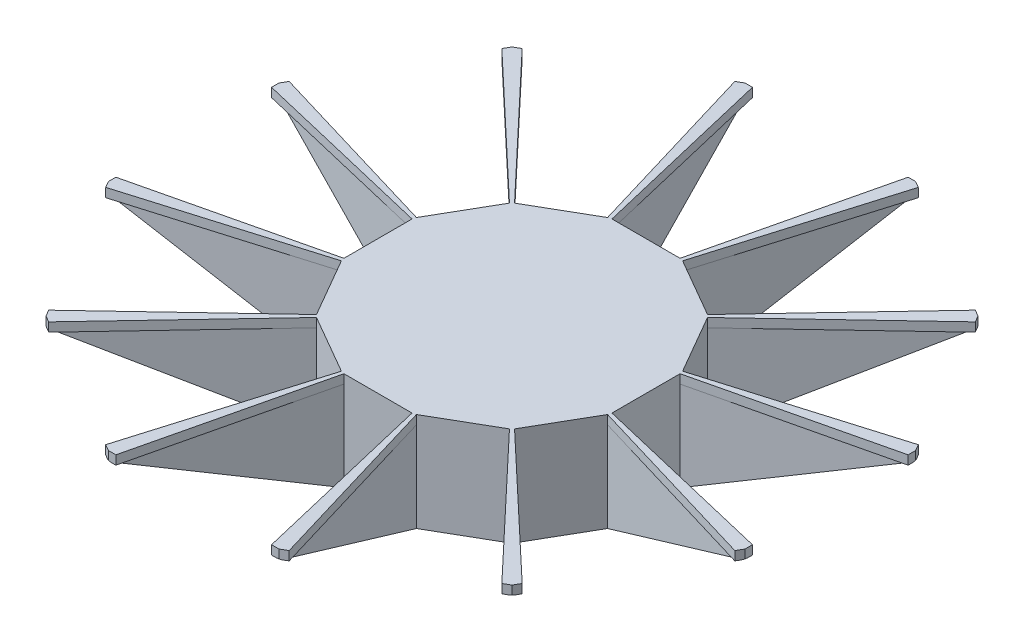
SolidWorks part; units mm, degrees
material "6061 Alloy"
ref_plane "Front Plane" through (0, 0, 0) normal (0, 0, 1) x (1, 0, 0)
ref_plane "Top Plane" through (0, 0, 0) normal (0, 1, 0) x (1, 0, 0)
ref_plane "Right Plane" through (0, 0, 0) normal (1, 0, 0) x (0, 0, -1)
sketch "Sketch1" plane through (0, 0, 0) normal (0, 1, 0) x (1, 0, 0)
  line L0 (-54.641, -54.641) -> (-20, -74.641) construction
  line L1 (54.641, 54.641) -> (20, 74.641) construction
  line L2 (20, 74.641) -> (-20, 74.641) construction
  line L3 (-20, 74.641) -> (-54.641, 54.641) construction
  line L4 (-54.641, 54.641) -> (-74.641, 20) construction
  line L5 (-74.641, 20) -> (-74.641, -20) construction
  line L6 (-74.641, -20) -> (-54.641, -54.641) construction
  line L7 (-20, -74.641) -> (20, -74.641) construction
  line L8 (20, -74.641) -> (54.641, -54.641) construction
  line L9 (54.641, -54.641) -> (74.641, -20) construction
  line L10 (74.641, -20) -> (74.641, 20) construction
  line L11 (74.641, 20) -> (54.641, 54.641) construction
  line L12 (-51.0863, 175.2019) -> (-20.8966, 74.1234)
  line L25 (47.5, 177.2724) -> (-47.5, 177.2724) construction
  line L26 (-47.5, 177.2724) -> (-129.7724, 129.7724) construction
  line L27 (-129.7724, 129.7724) -> (-177.2724, 47.5) construction
  line L28 (-177.2724, 47.5) -> (-177.2724, -47.5) construction
  line L29 (-177.2724, -47.5) -> (-129.7724, -129.7724) construction
  line L30 (-129.7724, -129.7724) -> (-47.5, -177.2724) construction
  line L31 (-47.5, -177.2724) -> (47.5, -177.2724) construction
  line L32 (47.5, -177.2724) -> (129.7724, -129.7724) construction
  line L33 (129.7724, -129.7724) -> (177.2724, -47.5) construction
  line L34 (177.2724, -47.5) -> (177.2724, 47.5) construction
  line L35 (177.2724, 47.5) -> (129.7724, 129.7724) construction
  line L36 (129.7724, 129.7724) -> (47.5, 177.2724) construction
  line L37 (-43.3589, 177.2724) -> (-18.9647, 74.641)
  line L38 (0, 0) -> (-47.5, 177.2724) construction
  line L39 (51.0863, 175.2019) -> (20.8966, 74.1234)
  line L40 (43.3589, 177.2724) -> (18.9647, 74.641)
  line L41 (131.843, 126.1861) -> (55.1587, 53.7444)
  line L42 (126.1861, 131.843) -> (53.7444, 55.1587)
  line L43 (177.2724, 43.3589) -> (74.641, 18.9647)
  line L44 (175.2019, 51.0863) -> (74.1234, 20.8966)
  line L45 (175.2019, -51.0863) -> (74.1234, -20.8966)
  line L46 (177.2724, -43.3589) -> (74.641, -18.9647)
  line L47 (126.1861, -131.843) -> (53.7444, -55.1587)
  line L48 (131.843, -126.1861) -> (55.1587, -53.7444)
  line L49 (43.3589, -177.2724) -> (18.9647, -74.641)
  line L50 (51.0863, -175.2019) -> (20.8966, -74.1234)
  line L51 (-51.0863, -175.2019) -> (-20.8966, -74.1234)
  line L52 (-43.3589, -177.2724) -> (-18.9647, -74.641)
  line L53 (-131.843, -126.1861) -> (-55.1587, -53.7444)
  line L54 (-126.1861, -131.843) -> (-53.7444, -55.1587)
  line L55 (-177.2724, -43.3589) -> (-74.641, -18.9647)
  line L56 (-175.2019, -51.0863) -> (-74.1234, -20.8966)
  line L57 (-175.2019, 51.0863) -> (-74.1234, 20.8966)
  line L58 (-177.2724, 43.3589) -> (-74.641, 18.9647)
  line L59 (-126.1861, 131.843) -> (-53.7444, 55.1587)
  line L60 (-131.843, 126.1861) -> (-55.1587, 53.7444)
  line L61 (-51.0863, 175.2019) -> (-47.5, 177.2724)
  line L62 (-47.5, 177.2724) -> (-43.3589, 177.2724)
  line L63 (43.3589, 177.2724) -> (47.5, 177.2724)
  line L64 (47.5, 177.2724) -> (51.0863, 175.2019)
  line L65 (126.1861, 131.843) -> (129.7724, 129.7724)
  line L66 (129.7724, 129.7724) -> (131.843, 126.1861)
  line L67 (175.2019, 51.0863) -> (177.2724, 47.5)
  line L68 (177.2724, 47.5) -> (177.2724, 43.3589)
  line L69 (177.2724, -43.3589) -> (177.2724, -47.5)
  line L70 (177.2724, -47.5) -> (175.2019, -51.0863)
  line L71 (131.843, -126.1861) -> (129.7724, -129.7724)
  line L72 (129.7724, -129.7724) -> (126.1861, -131.843)
  line L73 (51.0863, -175.2019) -> (47.5, -177.2724)
  line L74 (47.5, -177.2724) -> (43.3589, -177.2724)
  line L75 (-43.3589, -177.2724) -> (-47.5, -177.2724)
  line L76 (-47.5, -177.2724) -> (-51.0863, -175.2019)
  line L77 (-126.1861, -131.843) -> (-129.7724, -129.7724)
  line L78 (-129.7724, -129.7724) -> (-131.843, -126.1861)
  line L79 (-175.2019, -51.0863) -> (-177.2724, -47.5)
  line L80 (-177.2724, -47.5) -> (-177.2724, -43.3589)
  line L81 (-177.2724, 43.3589) -> (-177.2724, 47.5)
  line L82 (-177.2724, 47.5) -> (-175.2019, 51.0863)
  line L83 (-131.843, 126.1861) -> (-129.7724, 129.7724)
  line L84 (-129.7724, 129.7724) -> (-126.1861, 131.843)
  line L85 (-74.1234, 20.8966) -> (-55.1587, 53.7444)
  line L86 (-53.7444, 55.1587) -> (-20.8966, 74.1234)
  line L87 (-18.9647, 74.641) -> (18.9647, 74.641)
  line L88 (20.8966, 74.1234) -> (53.7444, 55.1587)
  line L89 (55.1587, 53.7444) -> (74.1234, 20.8966)
  line L90 (74.641, 18.9647) -> (74.641, -18.9647)
  line L91 (74.1234, -20.8966) -> (55.1587, -53.7444)
  line L92 (53.7444, -55.1587) -> (20.8966, -74.1234)
  line L93 (18.9647, -74.641) -> (-18.9647, -74.641)
  line L94 (-20.8966, -74.1234) -> (-53.7444, -55.1587)
  line L95 (-55.1587, -53.7444) -> (-74.1234, -20.8966)
  line L96 (-74.641, -18.9647) -> (-74.641, 18.9647)
  circle A0 centre (0, 0) radius 74.641 construction
  circle A1 centre (0, 0) radius 177.2724 construction
  point P1 (0, 177.2724)
  point P36 (0, 74.641)
  dimension "D1" = 40
  dimension "D2" = 95
  dimension "D3" = 8
  dimension "D4" = 2
  dimension "D5" = 12
  dimension "D6" = 12
  dimension "D7" = 12
extrude "Boss-Extrude1" add sketch "Sketch1" along normal blind 5
sketch "Sketch2" plane through (0, 0, 0) normal (0, -1, 0) x (1, 0, 0)
  line L0 (-20.8966, 74.1234) -> (-48.3966, 176.7548)
  line L1 (-20, 74.641) -> (-54.641, 54.641) construction
  line L2 (-54.641, 54.641) -> (-74.641, 20) construction
  line L3 (-74.641, 20) -> (-74.641, -20) construction
  line L4 (-74.641, -20) -> (-54.641, -54.641) construction
  line L5 (-54.641, -54.641) -> (-20, -74.641) construction
  line L6 (-20, -74.641) -> (20, -74.641) construction
  line L7 (20, -74.641) -> (54.641, -54.641) construction
  line L8 (54.641, -54.641) -> (74.641, -20) construction
  line L9 (74.641, -20) -> (74.641, 20) construction
  line L10 (74.641, 20) -> (54.641, 54.641) construction
  line L11 (54.641, 54.641) -> (20, 74.641) construction
  line L12 (20, 74.641) -> (-20, 74.641) construction
  line L13 (-51.0863, 175.2019) -> (-47.5, 177.2724) construction
  line L14 (-18.9647, 74.641) -> (-46.4647, 177.2724)
  line L16 (-47.5, 177.2724) -> (-43.3589, 177.2724) construction
  line L17 (-47.5, 177.2724) -> (-20, 74.641) construction
  line L18 (-48.3966, 176.7548) -> (-47.5, 177.2724)
  line L19 (-47.5, 177.2724) -> (-46.4647, 177.2724)
  line L20 (-20.8966, 74.1234) -> (-53.7444, 55.1587)
  line L21 (18.9647, 74.641) -> (46.4647, 177.2724)
  line L22 (-19.3301, 72.141) -> (-52.8109, 52.8109)
  line L23 (-52.8109, 52.8109) -> (-72.141, 19.3301)
  line L24 (-72.141, 19.3301) -> (-72.141, -19.3301)
  line L25 (-72.141, -19.3301) -> (-52.8109, -52.8109)
  line L26 (-52.8109, -52.8109) -> (-19.3301, -72.141)
  line L27 (-19.3301, -72.141) -> (19.3301, -72.141)
  line L28 (19.3301, -72.141) -> (52.8109, -52.8109)
  line L29 (52.8109, -52.8109) -> (72.141, -19.3301)
  line L30 (72.141, -19.3301) -> (72.141, 19.3301)
  line L31 (72.141, 19.3301) -> (52.8109, 52.8109)
  line L32 (52.8109, 52.8109) -> (19.3301, 72.141)
  line L33 (19.3301, 72.141) -> (-19.3301, 72.141)
  line L34 (20.8966, 74.1234) -> (48.3966, 176.7548)
  line L35 (18.9647, 74.641) -> (-18.9647, 74.641)
  line L36 (46.4647, 177.2724) -> (47.5, 177.2724)
  line L37 (47.5, 177.2724) -> (48.3966, 176.7548)
  line L38 (53.7444, 55.1587) -> (128.8758, 130.2901)
  line L39 (55.1587, 53.7444) -> (130.2901, 128.8758)
  line L40 (53.7444, 55.1587) -> (20.8966, 74.1234)
  line L41 (128.8758, 130.2901) -> (129.7724, 129.7724)
  line L42 (129.7724, 129.7724) -> (130.2901, 128.8758)
  line L43 (74.1234, 20.8966) -> (176.7548, 48.3966)
  line L44 (74.641, 18.9647) -> (177.2724, 46.4647)
  line L45 (74.1234, 20.8966) -> (55.1587, 53.7444)
  line L46 (176.7548, 48.3966) -> (177.2724, 47.5)
  line L47 (177.2724, 47.5) -> (177.2724, 46.4647)
  line L48 (74.641, -18.9647) -> (177.2724, -46.4647)
  line L49 (74.1234, -20.8966) -> (176.7548, -48.3966)
  line L50 (74.641, -18.9647) -> (74.641, 18.9647)
  line L51 (177.2724, -46.4647) -> (177.2724, -47.5)
  line L52 (177.2724, -47.5) -> (176.7548, -48.3966)
  line L53 (55.1587, -53.7444) -> (130.2901, -128.8758)
  line L54 (53.7444, -55.1587) -> (128.8758, -130.2901)
  line L55 (55.1587, -53.7444) -> (74.1234, -20.8966)
  line L56 (130.2901, -128.8758) -> (129.7724, -129.7724)
  line L57 (129.7724, -129.7724) -> (128.8758, -130.2901)
  line L58 (20.8966, -74.1234) -> (48.3966, -176.7548)
  line L59 (18.9647, -74.641) -> (46.4647, -177.2724)
  line L60 (20.8966, -74.1234) -> (53.7444, -55.1587)
  line L61 (48.3966, -176.7548) -> (47.5, -177.2724)
  line L62 (47.5, -177.2724) -> (46.4647, -177.2724)
  line L63 (-18.9647, -74.641) -> (-46.4647, -177.2724)
  line L64 (-20.8966, -74.1234) -> (-48.3966, -176.7548)
  line L65 (-18.9647, -74.641) -> (18.9647, -74.641)
  line L66 (-46.4647, -177.2724) -> (-47.5, -177.2724)
  line L67 (-47.5, -177.2724) -> (-48.3966, -176.7548)
  line L68 (-53.7444, -55.1587) -> (-128.8758, -130.2901)
  line L69 (-55.1587, -53.7444) -> (-130.2901, -128.8758)
  line L70 (-53.7444, -55.1587) -> (-20.8966, -74.1234)
  line L71 (-128.8758, -130.2901) -> (-129.7724, -129.7724)
  line L72 (-129.7724, -129.7724) -> (-130.2901, -128.8758)
  line L73 (-74.1234, -20.8966) -> (-176.7548, -48.3966)
  line L74 (-74.641, -18.9647) -> (-177.2724, -46.4647)
  line L75 (-74.1234, -20.8966) -> (-55.1587, -53.7444)
  line L76 (-176.7548, -48.3966) -> (-177.2724, -47.5)
  line L77 (-177.2724, -47.5) -> (-177.2724, -46.4647)
  line L78 (-74.641, 18.9647) -> (-177.2724, 46.4647)
  line L79 (-74.1234, 20.8966) -> (-176.7548, 48.3966)
  line L80 (-74.641, 18.9647) -> (-74.641, -18.9647)
  line L81 (-177.2724, 46.4647) -> (-177.2724, 47.5)
  line L82 (-177.2724, 47.5) -> (-176.7548, 48.3966)
  line L83 (-55.1587, 53.7444) -> (-130.2901, 128.8758)
  line L84 (-53.7444, 55.1587) -> (-128.8758, 130.2901)
  line L85 (-55.1587, 53.7444) -> (-74.1234, 20.8966)
  line L86 (-130.2901, 128.8758) -> (-129.7724, 129.7724)
  line L87 (-129.7724, 129.7724) -> (-128.8758, 130.2901)
  line L88 (-129.7724, 129.7724) -> (-126.1861, 131.843) construction
  line L89 (-131.843, 126.1861) -> (-129.7724, 129.7724) construction
  circle A0 centre (0, 0) radius 74.641 construction
  circle A1 centre (0, 0) radius 72.141 construction
  circle A2 centre (0, 0) radius 22.5
  point P2 (0, 72.141)
  dimension "D4" = 45
  dimension "D1" = 40
  dimension "D2" = 2.5
  dimension "D3" = 12
extrude "Boss-Extrude2" add sketch "Sketch2" along normal blind 50 contours L87 L86 L83 L85 L79 L82 L81 L78 L80 L74 L77 L76 L73 L75 L69 L72 L71 L68 L70 L64 L67 L66 L63 L65 L59 L62 L61 L58 L60 L54 L57 L56 L53 L55 L49 L52 L51 L48 L50 L44 L47 L46 L43 L45 L39 L42 L41 L38 L40 L34 L37 | A2
sketch "Sketch4" plane through (0.7071, 0, 0.7071) normal (0.7071, 0, 0.7071) x (0.7071, 0, -0.7071)
  line L0 (-185.0061, 0.8808) -> (-77.0061, -50)
  line L4 (-185.0061, 0.8808) -> (-185.0061, -50)
  line L5 (-185.0061, -50) -> (-77.0061, -50)
  dimension "D1" = 108
  dimension "D2" = 25.226
extrude "Cut-Extrude2" cut sketch "Sketch4" against normal up to next
pattern_circular "CirPattern1" count 12 over 360 about axis through (0, 0, 0) along (0, 1, 0) of "Cut-Extrude2"
sketch "Sketch5" plane through (0, -50, 0) normal (0, -1, 0) x (1, 0, 0)
  circle A0 centre (0, 0) radius 17.5
  circle A1 centre (0, 0) radius 10
  dimension "D1" = 35
  dimension "D2" = 20
extrude "Cut-Extrude4" cut sketch "Sketch5" against normal blind 4
sketch "Sketch6" plane through (0, -50, 0) normal (0, -1, 0) x (1, 0, 0)
  circle A0 centre (0, 0) radius 10
  dimension "D1" = 20
extrude "Boss-Extrude3" add sketch "Sketch6" along normal blind 30
sketch "Sketch7" plane through (0, -80, 0) normal (0, -1, 0) x (1, 0, 0)
  circle A0 centre (0, 0) radius 3
  dimension "D1" = 6
extrude "Cut-Extrude5" cut sketch "Sketch7" against normal blind 28.3
ref_plane "Plane1" through (0, 0, -10) normal (0, 0, -1) x (-1, 0, 0)
sketch "Sketch8" plane through (0, 0, -10) normal (0, 0, -1) x (-1, 0, 0)
  line L0 (-10, -80) -> (10, -80) construction
  line L1 (-10, -46) -> (-10, -80) construction
  circle A0 centre (0, -59.7) radius 1.75
  dimension "D2" = 3.5
  dimension "D1" = 20.3
  dimension "D3" = 10
extrude "Cut-Extrude6" cut sketch "Sketch8" against normal through all
